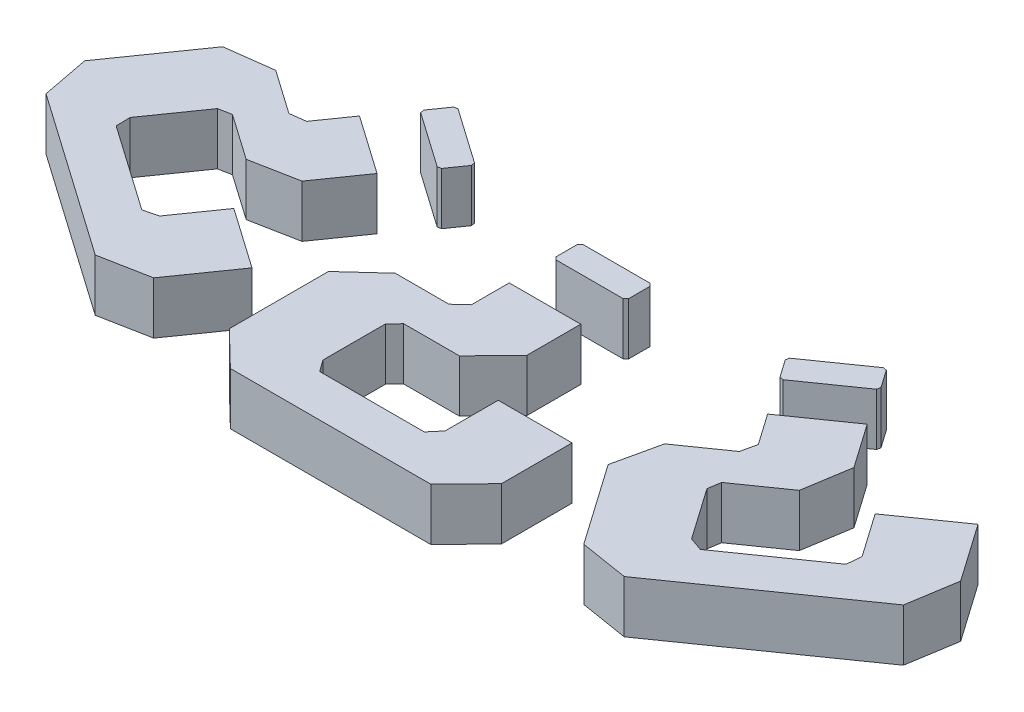
SolidWorks part; units mm, degrees
ref_plane "前视基准面" through (0, 0, 0) normal (0, 0, 1) x (1, 0, 0)
ref_plane "上视基准面" through (0, 0, 0) normal (0, 1, 0) x (1, 0, 0)
ref_plane "右视基准面" through (0, 0, 0) normal (1, 0, 0) x (0, 0, -1)
sketch "草图1" plane through (0, 0, 0) normal (0, 1, 0) x (1, 0, 0)
  line L0 (101.1546, 87.1483) -> (-215.5121, 87.1483) construction
  line L1 (133.8783, -67.6927) -> (133.8783, -72.3076) construction
  line L2 (133.8783, -72.3076) -> (131.6499, -74.6052) construction
  line L3 (131.6499, -74.6052) -> (119.8041, -74.6052) construction
  line L4 (119.8041, -74.6052) -> (117.5543, -72.4232) construction
  line L5 (117.5543, -72.4232) -> (117.5543, -66.3862) construction
  line L6 (117.5543, -66.3862) -> (119.8041, -64.3304) construction
  line L7 (119.8041, -64.3304) -> (122.8854, -64.3304) construction
  line L8 (122.8854, -64.3304) -> (123.3164, -63.9366) construction
  line L9 (123.3164, -63.9366) -> (123.3164, -61.5374) construction
  line L10 (123.3164, -61.5374) -> (128.2226, -61.5374) construction
  line L11 (128.2226, -61.5374) -> (128.2226, -65.1955) construction
  line L12 (128.2226, -65.1955) -> (126.0852, -67.3992) construction
  line L13 (126.0852, -67.3992) -> (122.8854, -67.3992) construction
  line L14 (122.8854, -67.3992) -> (122.6008, -67.6927) construction
  line L15 (122.6008, -67.6927) -> (122.6008, -70.9985) construction
  line L16 (122.6008, -70.9985) -> (122.8854, -71.3911) construction
  line L17 (122.8854, -71.3911) -> (128.5038, -71.3911) construction
  line L18 (128.5038, -71.3911) -> (128.8367, -70.9985) construction
  line L19 (128.8367, -70.9985) -> (128.8367, -67.6927) construction
  line L20 (128.8367, -67.6927) -> (133.8783, -67.6927) construction
  line L22 (127.9376, -59.8494) -> (128.3276, -59.4594) construction
  line L23 (127.9376, -59.8494) -> (123.7504, -59.8494) construction
  line L24 (128.3276, -59.4594) -> (128.3276, -57.8994) construction
  line L25 (127.9376, -57.5094) -> (123.7504, -57.5094) construction
  line L26 (123.3604, -59.4594) -> (123.3604, -57.8994) construction
  line L27 (133.4783, -68.0927) -> (133.4783, -72.1455)
  line L28 (133.4783, -72.1455) -> (131.4806, -74.2052)
  line L29 (123.7504, -59.8494) -> (123.3604, -59.4594) construction
  line L30 (123.3604, -57.8994) -> (123.7504, -57.5094) construction
  line L31 (128.3276, -57.8994) -> (127.9376, -57.5094) construction
  line L32 (143.2193, -61.1257) -> (142.7325, -64.1568) construction
  line L33 (138.5773, -54.993) -> (135.1473, -57.3947) construction
  line L34 (135.1633, -68.2201) -> (135.827, -65.2457) construction
  line L35 (147.0508, -65.527) -> (145.1547, -62.819) construction
  line L36 (131.4806, -74.2052) -> (119.9662, -74.2052)
  line L37 (135.827, -65.2457) -> (138.3511, -63.4783) construction
  line L38 (140.0465, -66.3958) -> (141.9426, -69.1037) construction
  line L39 (139.9194, -56.9098) -> (140.0152, -56.3667) construction
  line L40 (149.2845, -59.9273) -> (151.9315, -63.7076) construction
  line L42 (142.401, -69.2621) -> (147.0032, -66.0395) construction
  line L43 (151.424, -66.8678) -> (141.7204, -73.6623) construction
  line L44 (135.9463, -59.2157) -> (135.0516, -57.9379) construction
  line L45 (138.4783, -62.9085) -> (137.1022, -60.9433) construction
  line L46 (119.9662, -74.2052) -> (117.9543, -72.2539)
  line L47 (141.9426, -69.1037) -> (142.401, -69.2621) construction
  line L48 (140.0152, -56.3667) -> (139.1204, -55.0888) construction
  line L49 (142.7325, -64.1568) -> (140.1114, -65.9921) construction
  line L50 (147.0032, -66.0395) -> (147.0508, -65.527) construction
  line L51 (137.1022, -60.9433) -> (141.1211, -58.1292) construction
  line L52 (136.4895, -59.3115) -> (135.9463, -59.2157) construction
  line L53 (141.1211, -58.1292) -> (143.2193, -61.1257) construction
  line L54 (138.3511, -63.4783) -> (138.4783, -62.9085) construction
  line L55 (139.9194, -56.9098) -> (136.4895, -59.3115) construction
  line L56 (151.9315, -63.7076) -> (151.424, -66.8678) construction
  line L57 (141.7204, -73.6623) -> (138.626, -73.1653) construction
  line L58 (139.1204, -55.0888) -> (138.5773, -54.993) construction
  line L59 (138.626, -73.1653) -> (135.1633, -68.2201) construction
  line L60 (140.1114, -65.9921) -> (140.0465, -66.3958) construction
  line L61 (145.1547, -62.819) -> (149.2845, -59.9273) construction
  line L62 (135.0516, -57.9379) -> (135.1473, -57.3947) construction
  line L63 (112.935, -63.1899) -> (109.9202, -63.7692) construction
  line L64 (117.1102, -56.7304) -> (113.6803, -54.3287) construction
  line L65 (103.5131, -58.0463) -> (106.5352, -57.6526) construction
  line L66 (110.1097, -68.2957) -> (112.0058, -65.5878) construction
  line L67 (117.9543, -72.2539) -> (117.9543, -66.5626)
  line L68 (106.5352, -57.6526) -> (109.0593, -59.42) construction
  line L69 (106.8976, -62.011) -> (105.0015, -64.7189) construction
  line L70 (115.768, -58.6472) -> (116.3112, -58.5514) construction
  line L71 (116.1356, -68.4795) -> (113.4886, -72.2598) construction
  line L73 (105.0095, -65.2038) -> (109.6117, -68.4263) construction
  line L74 (110.3453, -72.8637) -> (100.6418, -66.0692) construction
  line L75 (112.2423, -55.7023) -> (113.1371, -54.4245) construction
  line L76 (109.6382, -59.3446) -> (111.0143, -57.3793) construction
  line L77 (117.9543, -66.5626) -> (119.9593, -64.7304)
  line L78 (105.0015, -64.7189) -> (105.0095, -65.2038) construction
  line L79 (116.3112, -58.5514) -> (117.206, -57.2735) construction
  line L80 (109.9202, -63.7692) -> (107.2991, -61.9339) construction
  line L81 (109.6117, -68.4263) -> (110.1097, -68.2957) construction
  line L82 (111.0143, -57.3793) -> (115.0332, -60.1934) construction
  line L83 (112.3381, -56.2455) -> (112.2423, -55.7023) construction
  line L84 (115.0332, -60.1934) -> (112.935, -63.1899) construction
  line L85 (109.0593, -59.42) -> (109.6382, -59.3446) construction
  line L86 (115.768, -58.6472) -> (112.3381, -56.2455) construction
  line L87 (113.4886, -72.2598) -> (110.3453, -72.8637) construction
  line L88 (100.6418, -66.0692) -> (100.0505, -62.9914) construction
  line L89 (117.206, -57.2735) -> (117.1102, -56.7304) construction
  line L90 (100.0505, -62.9914) -> (103.5131, -58.0463) construction
  line L91 (107.2991, -61.9339) -> (106.8976, -62.011) construction
  line L92 (112.0058, -65.5878) -> (116.1356, -68.4795) construction
  line L93 (113.1371, -54.4245) -> (113.6803, -54.3287) construction
  line L94 (119.9593, -64.7304) -> (123.0407, -64.7304)
  line L95 (123.0407, -64.7304) -> (123.7164, -64.1129)
  line L96 (123.7164, -64.1129) -> (123.7164, -61.9374)
  line L97 (123.7164, -61.9374) -> (127.8226, -61.9374)
  line L98 (127.8226, -61.9374) -> (127.8226, -65.0334)
  line L99 (127.8226, -65.0334) -> (125.9159, -66.9992)
  line L100 (125.9159, -66.9992) -> (122.7162, -66.9992)
  line L101 (122.7162, -66.9992) -> (122.2008, -67.5306)
  line L102 (122.2008, -67.5306) -> (122.2008, -71.1282)
  line L103 (122.2008, -71.1282) -> (122.6814, -71.7911)
  line L104 (122.6814, -71.7911) -> (128.689, -71.7911)
  line L105 (128.689, -71.7911) -> (129.2367, -71.1453)
  line L106 (129.2367, -71.1453) -> (129.2367, -68.0927)
  line L107 (129.2367, -68.0927) -> (133.4783, -68.0927)
  line L108 (127.772, -59.4494) -> (127.9276, -59.2937)
  line L109 (127.9276, -59.2937) -> (127.9276, -58.065)
  line L110 (127.9276, -58.065) -> (127.772, -57.9094)
  line L111 (127.772, -57.9094) -> (123.9161, -57.9094)
  line L112 (123.7604, -58.065) -> (123.9161, -57.9094)
  line L113 (123.7604, -59.2937) -> (123.7604, -58.065)
  line L114 (123.9161, -59.4494) -> (123.7604, -59.2937)
  line L115 (127.772, -59.4494) -> (123.9161, -59.4494)
  line L116 (142.7986, -61.2223) -> (142.3644, -63.9262)
  line L117 (142.3644, -63.9262) -> (139.7433, -65.7616)
  line L118 (139.7433, -65.7616) -> (139.6259, -66.4924)
  line L119 (139.6259, -66.4924) -> (141.6894, -69.4395)
  line L120 (141.6894, -69.4395) -> (142.4633, -69.7068)
  line L121 (142.4633, -69.7068) -> (147.3844, -66.2609)
  line L122 (147.3844, -66.2609) -> (147.4627, -65.4178)
  line L123 (147.4627, -65.4178) -> (145.7118, -62.9173)
  line L124 (145.7118, -62.9173) -> (149.1863, -60.4844)
  line L125 (149.1863, -60.4844) -> (151.5109, -63.8043)
  line L126 (151.5109, -63.8043) -> (151.0559, -66.6373)
  line L127 (151.0559, -66.6373) -> (141.6238, -73.2417)
  line L128 (141.6238, -73.2417) -> (138.8566, -72.7972)
  line L129 (138.8566, -72.7972) -> (135.5921, -68.1352)
  line L130 (135.5921, -68.1352) -> (136.1836, -65.4843)
  line L131 (136.1836, -65.4843) -> (138.7077, -63.7169)
  line L132 (138.7077, -63.7169) -> (138.9071, -62.8235)
  line L133 (138.9071, -62.8235) -> (137.6593, -61.0415)
  line L134 (137.6593, -61.0415) -> (141.0229, -58.6863)
  line L135 (141.0229, -58.6863) -> (142.7986, -61.2223)
  line L136 (138.671, -55.4157) -> (135.5125, -57.6273)
  line L137 (135.4742, -57.8441) -> (135.5125, -57.6273)
  line L138 (136.179, -58.8506) -> (135.4742, -57.8441)
  line L139 (136.3958, -58.8888) -> (136.179, -58.8506)
  line L140 (139.5543, -56.6772) -> (136.3958, -58.8888)
  line L141 (139.5543, -56.6772) -> (139.5925, -56.4604)
  line L142 (139.5925, -56.4604) -> (138.8878, -55.4539)
  line L143 (138.8878, -55.4539) -> (138.671, -55.4157)
  line L144 (112.7004, -62.8277) -> (110.011, -63.3444)
  line L145 (110.011, -63.3444) -> (107.3899, -61.5091)
  line L146 (107.3899, -61.5091) -> (106.6629, -61.6488)
  line L147 (106.6629, -61.6488) -> (104.5994, -64.5958)
  line L148 (104.5994, -64.5958) -> (104.6129, -65.4144)
  line L149 (104.6129, -65.4144) -> (109.534, -68.8602)
  line L150 (109.534, -68.8602) -> (110.3531, -68.6454)
  line L151 (110.3531, -68.6454) -> (112.104, -66.1449)
  line L152 (112.104, -66.1449) -> (115.5785, -68.5777)
  line L153 (115.5785, -68.5777) -> (113.2539, -71.8976)
  line L154 (113.2539, -71.8976) -> (110.4361, -72.439)
  line L155 (110.4361, -72.439) -> (101.004, -65.8346)
  line L156 (101.004, -65.8346) -> (100.4752, -63.0822)
  line L157 (100.4752, -63.0822) -> (103.7397, -58.4201)
  line L158 (103.7397, -58.4201) -> (106.4329, -58.0693)
  line L159 (106.4329, -58.0693) -> (108.9571, -59.8367)
  line L160 (108.9571, -59.8367) -> (109.8647, -59.7185)
  line L161 (109.8647, -59.7185) -> (111.1125, -57.9364)
  line L162 (111.1125, -57.9364) -> (114.4761, -60.2916)
  line L163 (114.4761, -60.2916) -> (112.7004, -62.8277)
  line L164 (116.7451, -56.963) -> (113.5865, -54.7514)
  line L165 (113.3697, -54.7896) -> (113.5865, -54.7514)
  line L166 (112.665, -55.7961) -> (113.3697, -54.7896)
  line L167 (112.7032, -56.0129) -> (112.665, -55.7961)
  line L168 (115.8617, -58.2245) -> (112.7032, -56.0129)
  line L169 (115.8617, -58.2245) -> (116.0786, -58.1863)
  line L170 (116.0786, -58.1863) -> (116.7833, -57.1798)
  line L171 (116.7833, -57.1798) -> (116.7451, -56.963)
  point P20 (125.844, -58.6794)
  point P54 (137.5334, -57.1523)
  point P88 (114.7241, -56.4879)
  dimension "D1" = 0.4
extrude "凸台-拉伸1" add sketch "草图1" along normal blind 3
